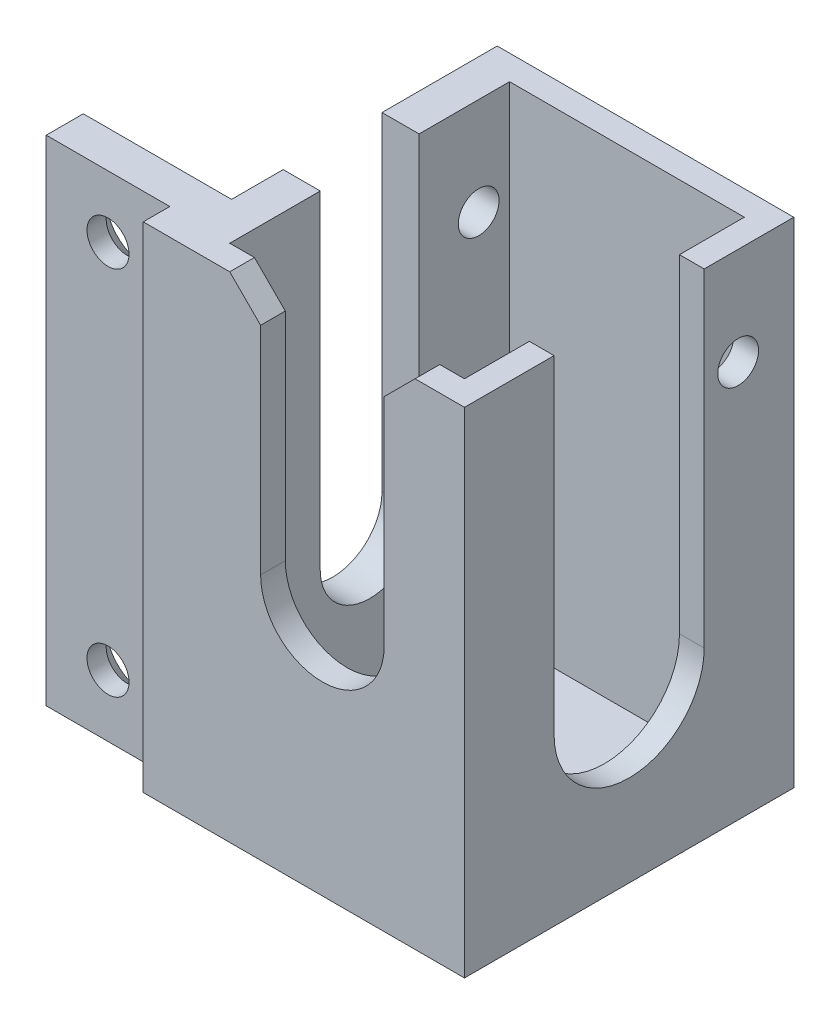
SolidWorks part; units mm, degrees
ref_plane "Front Plane" through (0, 0, 0) normal (0, 0, 1) x (1, 0, 0)
ref_plane "Top Plane" through (0, 0, 0) normal (0, 1, 0) x (1, 0, 0)
ref_plane "Right Plane" through (0, 0, 0) normal (1, 0, 0) x (0, 0, -1)
sketch "Sketch1" plane through (0, 0, 0) normal (0, 1, 0) x (1, 0, 0)
  line L21 (9.5, 11.325) -> (-9.5, 11.325)
  line L22 (-9.5, 11.325) -> (-9.5, -11.325)
  line L23 (-9.5, -11.325) -> (9.5, -11.325)
  line L24 (9.5, -11.325) -> (9.5, 11.325)
  line L25 (-14.5, -13.325) -> (11.5, -13.325)
  line L26 (11.5, -13.325) -> (11.5, 13.325)
  line L27 (11.5, 13.325) -> (-12.5, 13.325)
  line L28 (-12.5, 13.325) -> (-12.5, -8.175)
  line L29 (-12.5, -8.175) -> (-24.5, -8.175)
  line L30 (-24.5, -8.175) -> (-24.5, -11.175)
  line L31 (-24.5, -11.175) -> (-14.5, -11.175)
  line L32 (-14.5, -11.175) -> (-14.5, -13.325)
  line L33 (0, -11.325) -> (0, 11.325) construction
  point P31 (0, 0)
  dimension "D1" = 19
  dimension "D2" = 22.65
  dimension "D3" = 2
  dimension "D4" = 2
  dimension "D5" = 2
  dimension "D6" = 3
  dimension "D7" = 2
  dimension "D8" = 10
  dimension "D9" = 2.15
  dimension "D10" = 3
extrude "Boss-Extrude1" add sketch "Sketch1" along normal blind 40
sketch "Sketch2" plane through (0, 0, 0) normal (0, -1, 0) x (1, 0, 0)
  line L4 (9.5, 11.325) -> (9.5, -11.325) construction
  line L5 (-1.73, 2.75) -> (-1.73, -2.75)
  line L6 (-1.73, -2.75) -> (1.73, -2.75)
  line L7 (1.73, -2.75) -> (1.73, 2.75)
  line L8 (-14.5, 13.325) -> (-14.5, 11.175)
  line L9 (-14.5, 11.175) -> (-24.5, 11.175)
  line L10 (-24.5, 11.175) -> (-24.5, 8.175)
  line L11 (-24.5, 8.175) -> (-12.5, 8.175)
  line L12 (-12.5, 8.175) -> (-12.5, -13.325)
  line L13 (-12.5, -13.325) -> (11.5, -13.325)
  line L14 (11.5, -13.325) -> (11.5, 13.325)
  line L15 (11.5, 13.325) -> (-14.5, 13.325)
  line L16 (-14.5, 13.325) -> (-14.5, 11.175)
  line L17 (-14.5, 11.175) -> (-24.5, 11.175)
  line L18 (-24.5, 11.175) -> (-24.5, 8.175)
  line L19 (-24.5, 8.175) -> (-12.5, 8.175)
  line L20 (-12.5, 8.175) -> (-12.5, -13.325)
  line L21 (-12.5, -13.325) -> (11.5, -13.325)
  line L22 (11.5, -13.325) -> (11.5, 13.325)
  line L23 (11.5, 13.325) -> (-14.5, 13.325)
  line L24 (1.73, 2.75) -> (-1.73, 2.75)
  line L25 (0, -2.75) -> (0, 2.75) construction
  line L26 (-9.5, -11.325) -> (-9.5, 11.325) construction
  point P22 (0, 0)
  dimension "D2" = 3.46
  dimension "D3" = 5.5
  dimension "D1" = 0
extrude "Boss-Extrude2" add sketch "Sketch2" against normal blind 0.7
sketch "Sketch3" plane through (-12.5, 0, 0) normal (-1, 0, 0) x (0, 0, 1)
  line L0 (0, 46) -> (0, 13.43) construction
  line L1 (4, 46) -> (4, 13.43)
  line L2 (-4, 46) -> (-4, 13.43)
  line L3 (-13.325, 40) -> (8.175, 40) construction
  arc A0 (4, 46) -> (-4, 46) centre (0, 46) ccw
  arc A1 (-4, 13.43) -> (4, 13.43) centre (0, 13.43) ccw
  point P3 (0, 29.715)
  dimension "D1" = 8
  dimension "D2" = 26.57
  dimension "D3" = 6
extrude "Cut-Extrude1" cut sketch "Sketch3" against normal blind 3
sketch "Sketch4" plane through (9.5, 0, 0) normal (-1, 0, 0) x (0, 0, 1)
  line L0 (0, 43.3627) -> (0, 13.43) construction
  line L1 (6.075, 43.3627) -> (6.075, 13.43)
  line L2 (-6.075, 43.3627) -> (-6.075, 13.43)
  arc A0 (6.075, 43.3627) -> (-6.075, 43.3627) centre (0, 43.3627) ccw
  arc A1 (-6.075, 13.43) -> (6.075, 13.43) centre (0, 13.43) ccw
  point P3 (0, 28.3963)
  dimension "D1" = 12.15
extrude "Cut-Extrude2" cut sketch "Sketch4" against normal blind 2
sketch "Sketch5" plane through (0, 0, 13.325) normal (0, 0, 1) x (1, 0, 0)
  line L1 (-14.5, 40) -> (11.5, 40) construction
  line L2 (0, 47.9306) -> (0, 20) construction
  line L3 (5, 47.9306) -> (5, 20)
  line L4 (-5, 47.9306) -> (-5, 20)
  arc A0 (5, 47.9306) -> (-5, 47.9306) centre (0, 47.9306) ccw
  arc A1 (-5, 20) -> (5, 20) centre (0, 20) ccw
  point P5 (0, 33.9653)
  dimension "D1" = 10
  dimension "D2" = 20
extrude "Cut-Extrude3" cut sketch "Sketch5" against normal blind 2
sketch "Sketch7" plane through (-24.5, 0, 0) normal (-1, 0, 0) x (0, 0, 1)
  line L0 (8.175, 30) -> (10.175, 28)
  line L1 (8.175, 40) -> (8.175, 0) construction
  line L2 (10.175, 28) -> (10.175, 12)
  line L3 (10.175, 12) -> (8.175, 10)
  line L4 (8.175, 40) -> (11.175, 40) construction
  line L5 (8.175, 0) -> (11.175, 0) construction
  line L6 (11.175, 40) -> (11.175, 0) construction
  line L7 (8.175, 10) -> (8.175, 30)
  dimension "D1" = 45
  dimension "D2" = 45
  dimension "D3" = 10
  dimension "D4" = 10
  dimension "D5" = 1
extrude "Cut-Extrude4" cut sketch "Sketch7" against normal up to surface (12 mm away) up to face at (-12.5, 22.8575, -1.2875)
sketch "Sketch8" plane through (0, 0, 8.175) normal (0, 0, -1) x (-1, 0, 0)
  line L0 (24.5, 10) -> (14.5, 10) construction
  line L1 (12.5, 10) -> (24.5, 10) construction
  line L2 (14.5, 10) -> (24.5, 0) construction
  line L3 (12.5, 10) -> (12.5, 0) construction
  line L4 (24.5, 20) -> (33.6538, 20) construction
  line L5 (24.5, 12) -> (24.5, 28) construction
  point P10 (19.5, 5)
  point P18 (19.5, 35)
  dimension "D1" = 2
hole_wizard "CSK for M3 Flat Head Machine Screw2" positions "Sketch8" profile "Sketch13" countersink size "M3" standard "ANSI Metric"
sketch "Sketch13" plane through (-19.5, 35, 8.175) normal (1, 0, 0) x (0, 1, 0)
  line L0 (0, 0) -> (0, 16)
  line L1 (0, 16) -> (1.7, 14.9785)
  line L2 (1.7, 14.9785) -> (1.7, 1.45)
  line L3 (1.7, 1.45) -> (3.15, 0)
  line L5 (3.15, 0) -> (0, 0)
  line L6 (-1.7, 1.45) -> (-3.15, 0) construction
  line L10 (0, 16) -> (-1.7, 14.9785) construction
  line L11 (0, -6.35) -> (0, 107.95) construction
  dimension "Hole Dia." = 3.4
  dimension "Hole Depth" = 16
  dimension "Near C'Sink Dia." = 6.3
  dimension "Near C'Sink Angle" = 90
  dimension "Drill Angle" = 118
chamfer "Chamfer3" distance 2.5 angle 45 2 edges at (-5, 40, 12.325) (5, 40, 12.325)
sketch "Sketch14" plane through (-12.5, 0, 0) normal (-1, 0, 0) x (0, 0, 1)
  line L0 (-11.325, 40) -> (-11.325, 0.7) construction
  line L7 (11.325, 0.7) -> (-11.325, 0.7) construction
  circle A0 centre (-8.825, 32.1) radius 1.65
  dimension "D1" = 31.4
  dimension "D3" = 3.3
  dimension "D2" = 2.5
extrude "Cut-Extrude5" cut sketch "Sketch14" against normal through all both and the other way through all
